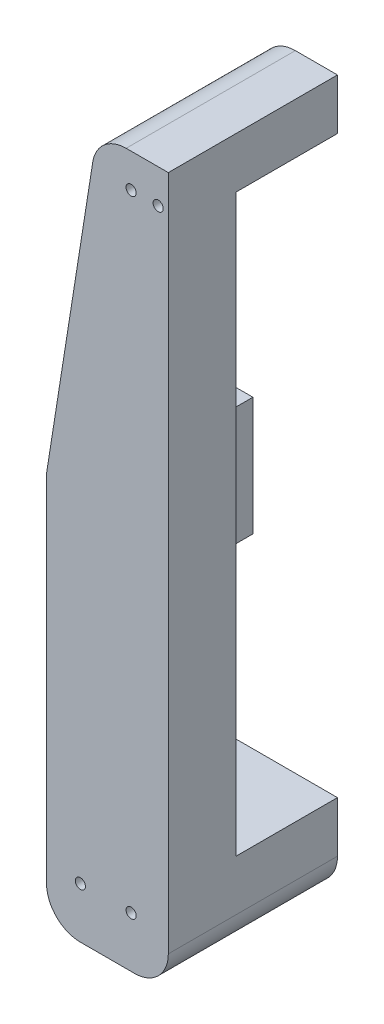
SolidWorks part; units mm, degrees
ref_plane "Alzado" through (0, 0, 0) normal (1, 0, 0) x (0, 1, 0)
ref_plane "Planta" through (0, 0, 0) normal (0, 0, 1) x (0, 1, 0)
ref_plane "Vista lateral" through (0, 0, 0) normal (0, 1, 0) x (-1, 0, 0)
sketch "Croquis1" plane through (0, 0, 0) normal (0, 0, 1) x (0, 1, 0)
  line L0 (0, 0) -> (-185, 0) construction
  line L1 (-85, 25) -> (10, 10)
  line L2 (10, -11) -> (-200, -11)
  line L3 (10, -11) -> (10, 10)
  line L4 (-85, 25) -> (-200, 25)
  line L5 (-200, -11) -> (-200, 25)
  line L7 (-165, 0) -> (-15, 0) construction
  line L8 (-165, 0) -> (-165, 28.5142) construction
  line L9 (-165, 28.5142) -> (-15, 28.5142) construction
  line L10 (-15, 0) -> (-15, 28.5142) construction
  circle A0 centre (0, 0) radius 1.5
  circle A1 centre (-185, 0) radius 1.5
  circle A2 centre (-185, 15) radius 1.5
  circle A3 centre (0, -8) radius 1.5
  dimension "D1" = 3
  dimension "D2" = 185
  dimension "D3" = 15
  dimension "D4" = 8
  dimension "D5" = 3
  dimension "D6" = 10
  dimension "D7" = 10
  dimension "D8" = 15
  dimension "D9" = 10
  dimension "D10" = 100
  dimension "D11" = 150
  dimension "D12" = 15
extrude "Saliente-Extruir1" add sketch "Croquis1" along normal blind 50
sketch "Croquis2" plane through (11, 0, 0) normal (1, 0, 0) x (0, 0, -1)
  line L0 (0, -200) -> (0, 10) construction
  line L1 (0, -5) -> (-30, -5)
  line L2 (0, -5) -> (0, -175)
  line L3 (0, -175) -> (-30, -175)
  line L4 (-30, -5) -> (-30, -175)
  line L5 (-50, -200) -> (0, -200) construction
  dimension "D1" = 5
  dimension "D2" = 25
  dimension "D3" = 30
extrude "Cortar-Extruir1" cut sketch "Croquis2" against normal up to next
fillet "Redondeo1" radius 10 2 edges at (11, -200, 25) (-25, -200, 25)
fillet "Redondeo2" radius 10 1 edges at (-10, 10, 25)
sketch "Croquis3" plane through (0, 0, 30) normal (0, 0, -1) x (-1, 0, 0)
  line L0 (0, 0) -> (0, -185) construction
  line L1 (12.3684, -5) -> (-11, -5) construction
  line L2 (14, -165) -> (-14, -165) construction
  line L3 (14, -165) -> (14, -15) construction
  line L4 (14, -15) -> (-14, -15) construction
  line L5 (-14, -165) -> (-14, -15) construction
  line L6 (0, -15) -> (0, -165) construction
  line L7 (14, -90) -> (-14, -90) construction
  line L8 (14, -90) -> (19, -90) construction
  line L10 (25, -85) -> (14, -85)
  line L11 (25, -85) -> (25, -120)
  line L12 (25, -120) -> (14, -120)
  line L13 (14, -85) -> (14, -120)
  circle A0 centre (19, -90) radius 1.5
  circle A1 centre (0, -145) radius 25 construction
  circle A2 centre (19, -110) radius 1.5
  point P4 (0, -90)
  dimension "D5" = 3
  dimension "D7" = 50
  dimension "D9" = 3
  dimension "D1" = 28
  dimension "D2" = 150
  dimension "D3" = 10
  dimension "D4" = 5
  dimension "D6" = 35
  dimension "D8" = 20
  dimension "D10" = 20
extrude "Saliente-Extruir2" add sketch "Croquis3" along normal blind 30
